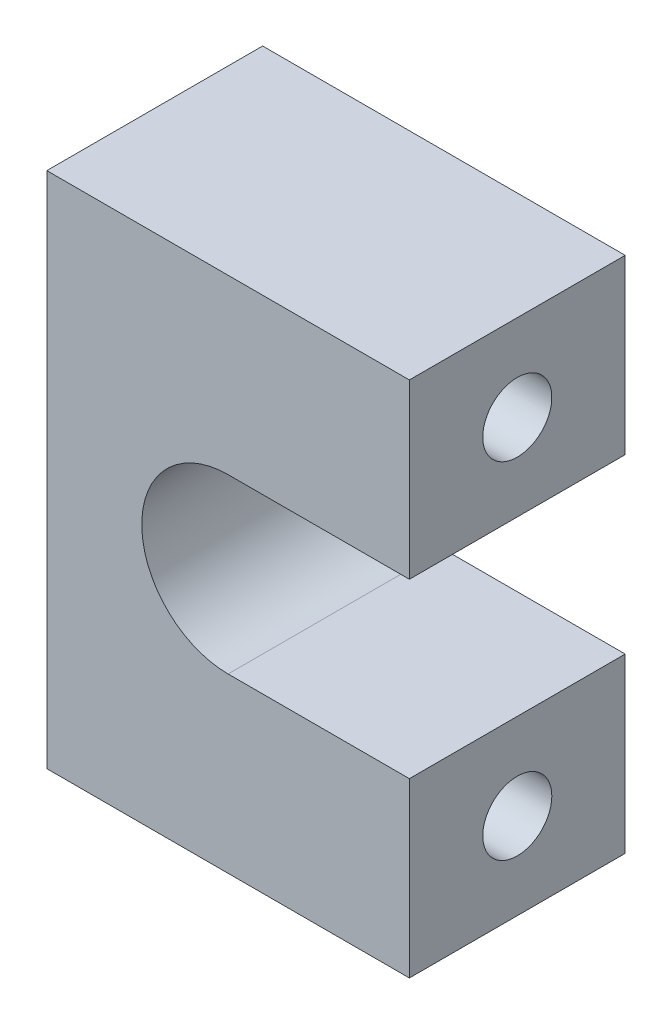
SolidWorks part; units mm, degrees
ref_plane "Front Plane" through (0, 0, 0) normal (0, 0, 1) x (1, 0, 0)
ref_plane "Top Plane" through (0, 0, 0) normal (0, 1, 0) x (1, 0, 0)
ref_plane "Right Plane" through (0, 0, 0) normal (1, 0, 0) x (0, 0, -1)
sketch "Sketch1" plane through (0, 0, 0) normal (0, 1, 0) x (1, 0, 0)
  line L1 (0, 0) -> (42, 0)
  line L2 (0, 0) -> (0, 25)
  line L3 (0, 25) -> (42, 25)
  line L4 (42, 0) -> (42, 25)
  dimension "D1" = 25
  dimension "D2" = 42
extrude "Boss-Extrude1" add sketch "Sketch1" along normal blind 60
sketch "Sketch2" plane through (0, 0, 0) normal (0, 0, 1) x (1, 0, 0)
  line L0 (42, 40) -> (21, 40)
  line L1 (42, 60) -> (42, 0) construction
  line L2 (42, 20) -> (21, 20)
  line L3 (0, 0) -> (42, 0) construction
  line L4 (42, 40) -> (42, 20)
  arc A0 (21, 20) -> (21, 40) centre (21, 30) cw
  dimension "D1" = 21
  dimension "D2" = 10
  dimension "D3" = 30
extrude "Cut-Extrude1" cut sketch "Sketch2" against normal blind 56
sketch "Sketch3" plane through (42, 0, 0) normal (1, 0, 0) x (0, 0, -1)
  line L0 (0, 30) -> (25, 30) construction
  line L1 (25, 20) -> (0, 20) construction
  line L2 (0, 0) -> (25, 0) construction
  line L3 (25, 20) -> (25, 0) construction
  circle A0 centre (12.5, 10) radius 4
  circle A1 centre (12.5, 50) radius 4
  dimension "D2" = 8
  dimension "D1" = 10
  dimension "D3" = 10
  dimension "D4" = 12.5
extrude "Cut-Extrude2" cut sketch "Sketch3" against normal blind 15
